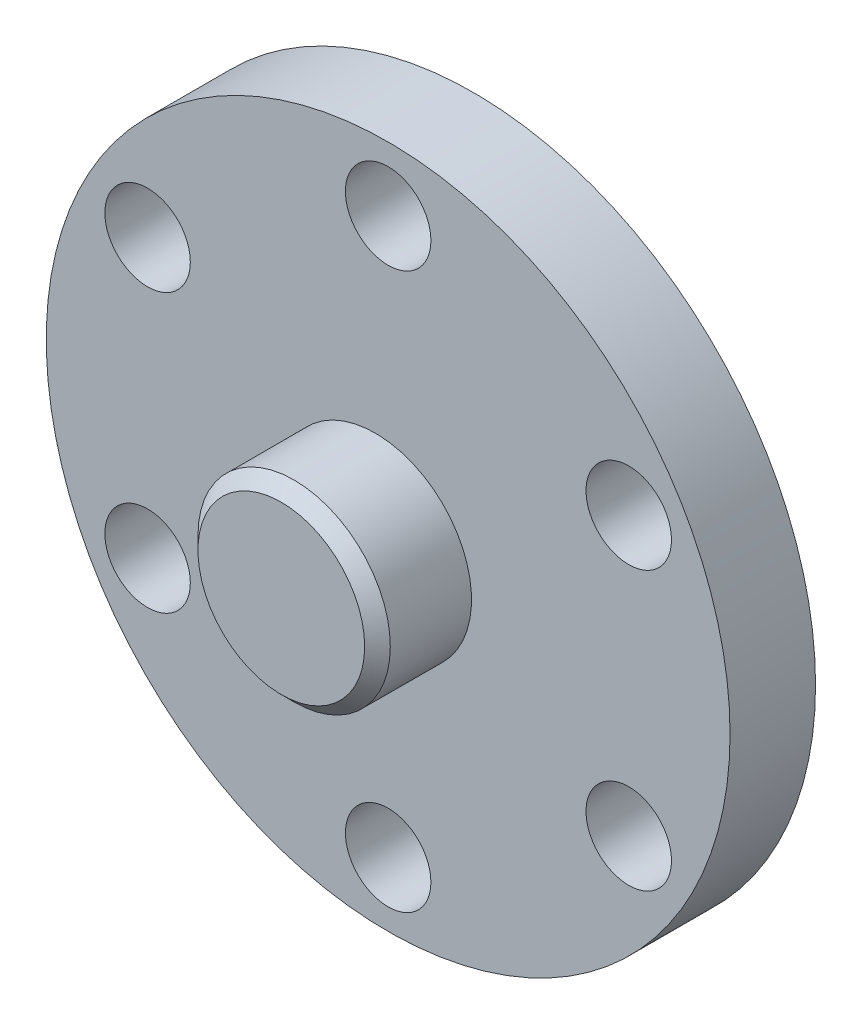
SolidWorks part; units mm, degrees
ref_plane "Front" through (0, 0, 0) normal (0, 0, 1) x (1, 0, 0)
ref_plane "Top" through (0, 0, 0) normal (0, 1, 0) x (1, 0, 0)
ref_plane "Right" through (0, 0, 0) normal (1, 0, 0) x (0, 0, -1)
sketch "Sketch1" plane through (0, 0, 0) normal (0, 0, 1) x (1, 0, 0)
  circle A0 centre (0, 0) radius 80
  dimension "D1" = 160
extrude "Base-Extrude" add sketch "Sketch1" along normal blind 20
sketch "Sketch2" plane through (0, 0, 0) normal (0, 1, 0) x (1, 0, 0)
  line L0 (0, 0) -> (0, -61.8831) construction
  line L1 (0, -20) -> (0, 0) construction
  line L2 (-10, -20) -> (-10, -23)
  line L3 (-80, -20) -> (80, -20) construction
  line L4 (-10, -23) -> (-22.5, -23)
  line L5 (-22.5, -23) -> (-22.5, -45)
  line L6 (-22.5, -45) -> (0, -45)
  line L7 (0, -45) -> (0, -20)
  line L8 (0, -20) -> (-10, -20)
  dimension "D1" = 45
  dimension "D2" = 25
  dimension "D3" = 20
  dimension "D4" = 22
revolve "Boss-Revolve1" add sketch "Sketch2" angle 360 about L0
chamfer "Chamfer1" distance 3 angle 45 1 edges at (-22.5, 0, 45)
sketch "Sketch3" plane through (0, 0, 20) normal (0, 0, 1) x (1, 0, 0)
  line L0 (0, 0) -> (0, 65) construction
  circle A1 centre (0, 0) radius 65 construction
  dimension "D1" = 130
hole_wizard "Ø20.0 (20) 直徑孔1" positions "3DSketch2" profile "Sketch5" hole size "Ø20.0" standard "Ansi Metric" end condition through all
sketch3d "3DSketch2"
  point P0 (0, 65, 20)
sketch "Sketch5" plane through (0, 65, 20) normal (1, 0, 0) x (0, -1, 0)
  line L0 (0, 0) -> (0, 20)
  line L1 (0, 20) -> (10, 20)
  line L2 (10, 20) -> (10, 0)
  line L5 (10, 0) -> (0, 0)
  line L11 (0, -6.35) -> (0, 107.95) construction
  dimension "Thru Hole Dia." = 20
  dimension "Thru Hole Depth" = 20
pattern_circular "CirPattern2" count 6 over 360 about axis through (0, 0, 0) along (0, 0, 1) of "Ø20.0 (20) 直徑孔1"
